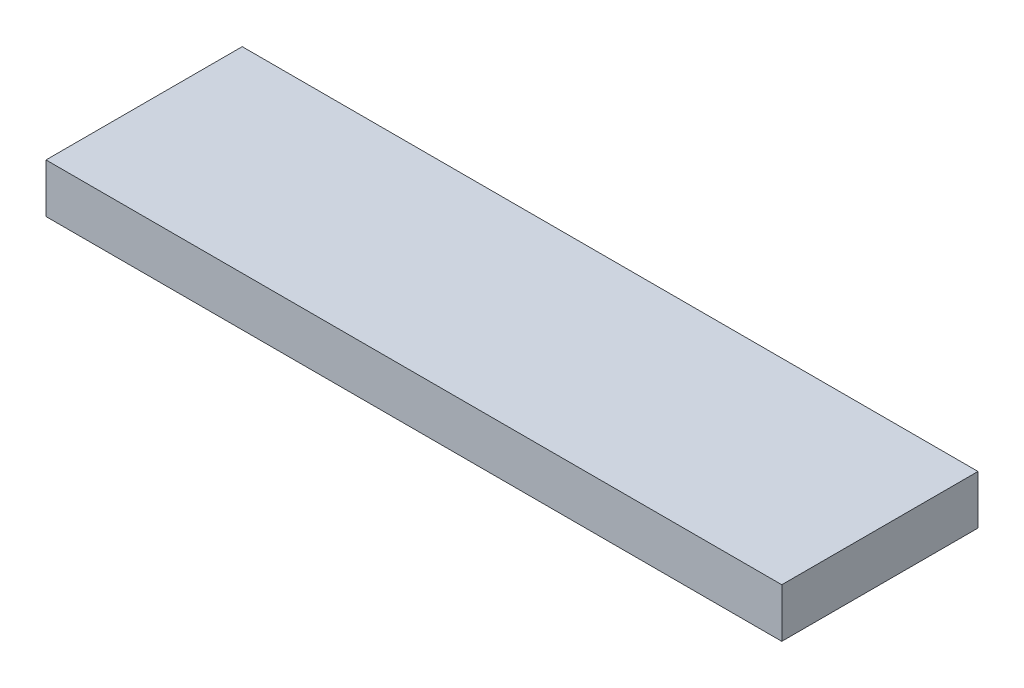
SolidWorks part; units mm, degrees
ref_plane "Front Plane" through (0, 0, 0) normal (0, 0, 1) x (1, 0, 0)
ref_plane "Top Plane" through (0, 0, 0) normal (0, 1, 0) x (1, 0, 0)
ref_plane "Right Plane" through (0, 0, 0) normal (1, 0, 0) x (0, 0, -1)
sketch "Sketch1" plane through (0, 0, 0) normal (0, 1, 0) x (1, 0, 0)
  line L1 (0, 0) -> (30, 0)
  line L2 (0, 0) -> (0, 8)
  line L3 (0, 8) -> (30, 8)
  line L4 (30, 0) -> (30, 8)
  dimension "D1" = 30
  dimension "D2" = 8
extrude "Boss-Extrude1" add sketch "Sketch1" along normal blind 2
